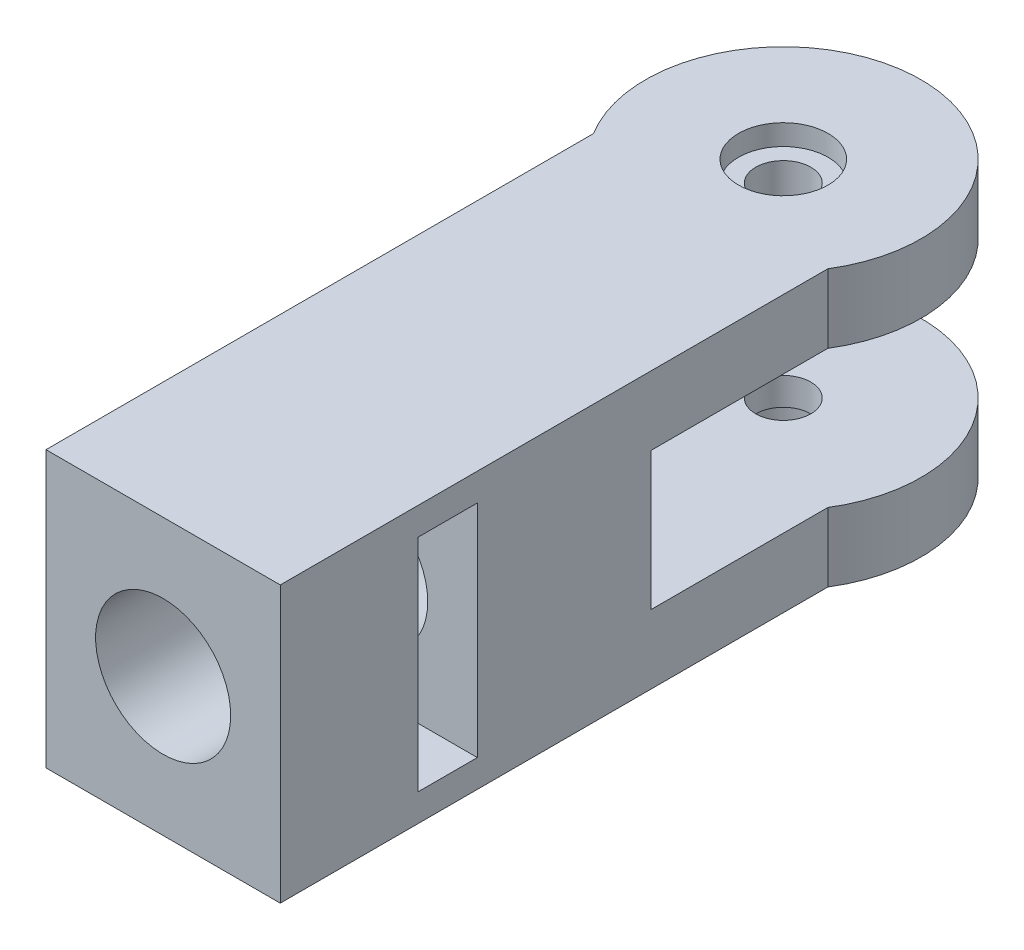
SolidWorks part; units mm, degrees
ref_plane "前视基准面" through (0, 0, 0) normal (0, 0, 1) x (1, 0, 0)
ref_plane "上视基准面" through (0, 0, 0) normal (0, 1, 0) x (1, 0, 0)
ref_plane "右视基准面" through (0, 0, 0) normal (1, 0, 0) x (0, 0, -1)
sketch "草图1" plane through (0, 0, 0) normal (0, 0, 1) x (1, 0, 0)
  line L1 (-19.3284, -7.3438) -> (-2.3284, -7.3438)
  line L2 (-19.3284, -7.3438) -> (-19.3284, -27.3438)
  line L3 (-19.3284, -27.3438) -> (-2.3284, -27.3438)
  line L4 (-2.3284, -7.3438) -> (-2.3284, -27.3438)
  dimension "D1" = 20
  dimension "D2" = 17
extrude "凸台-拉伸1" add sketch "草图1" along normal blind 40 contours L2 L1 L4 L3
sketch "草图3" plane through (0, -27.3438, 0) normal (0, -1, 0) x (1, 0, 0)
  line L1 (-19.3284, 0) -> (-2.3284, 0) construction
  circle A0 centre (-10.8284, -5) radius 2
  circle A1 centre (-10.8284, -5) radius 10
  point P7 (-10.8284, 0)
  dimension "D1" = 4
  dimension "D2" = 5
extrude "凸台-拉伸2" add sketch "草图3" against normal blind 10
sketch "草图4" plane through (0, -7.3438, 0) normal (0, 1, 0) x (1, 0, 0)
  circle A0 centre (-10.8284, 5) radius 2
  circle A1 centre (-10.8284, 5) radius 10
  circle A2 centre (-10.8284, 5) radius 2 construction
  dimension "D1" = 4
  dimension "D2" = 20
extrude "凸台-拉伸3" add sketch "草图4" against normal blind 5
sketch "草图5" plane through (0, -12.3438, 0) normal (0, -1, 0) x (1, 0, 0)
  circle A0 centre (-10.8284, -5) radius 20
  dimension "D1" = 40
extrude "切除-拉伸1" cut sketch "草图5" along normal blind 10
sketch "草图6" plane through (0, 0, 40) normal (0, 0, 1) x (1, 0, 0)
  line L0 (-2.3284, -7.3438) -> (-19.3284, -27.3438) construction
  line L1 (-19.3284, -27.3438) -> (-2.3284, -27.3438) construction
  line L2 (-2.3284, -27.3438) -> (-19.3284, -7.3438) construction
  line L3 (-19.3284, -7.3438) -> (-19.3284, -27.3438) construction
  line L4 (-19.3284, -7.3438) -> (-2.3284, -7.3438) construction
  circle A0 centre (-10.8284, -17.3438) radius 4.9
  point P14 (-10.8284, -17.3438)
  dimension "D1" = 9.8
extrude "切除-拉伸2" cut sketch "草图6" against normal up to next
sketch "草图7" plane through (-2.3284, 0, 0) normal (1, 0, 0) x (0, 0, -1)
  line L0 (-40, -7.3438) -> (-40, -27.3438) construction
  line L1 (-30, -9.3438) -> (-25.7, -9.3438)
  line L2 (-30, -9.3438) -> (-30, -25.3438)
  line L3 (-30, -25.3438) -> (-25.7, -25.3438)
  line L4 (-25.7, -9.3438) -> (-25.7, -25.3438)
  point P6 (-40, -17.3438)
  point P7 (-30, -17.3438)
  dimension "D1" = 16
  dimension "D2" = 4.3
  dimension "D3" = 10
extrude "切除-拉伸3" cut sketch "草图7" against normal up to next contours L2 L1 L4 L3
sketch "草图8" plane through (0, -27.3438, 0) normal (0, -1, 0) x (1, 0, 0)
  circle A0 centre (-10.8284, -5) radius 3.25
  dimension "D1" = 6.5
extrude "切除-拉伸4" cut sketch "草图8" against normal blind 3
sketch "草图9" plane through (0, -7.3438, 0) normal (0, 1, 0) x (1, 0, 0)
  circle A0 centre (-10.8284, 5) radius 3.25
  circle A1 centre (-10.8284, 5) radius 2 construction
  dimension "D1" = 6.5
extrude "切除-拉伸5" cut sketch "草图9" against normal blind 1.5
